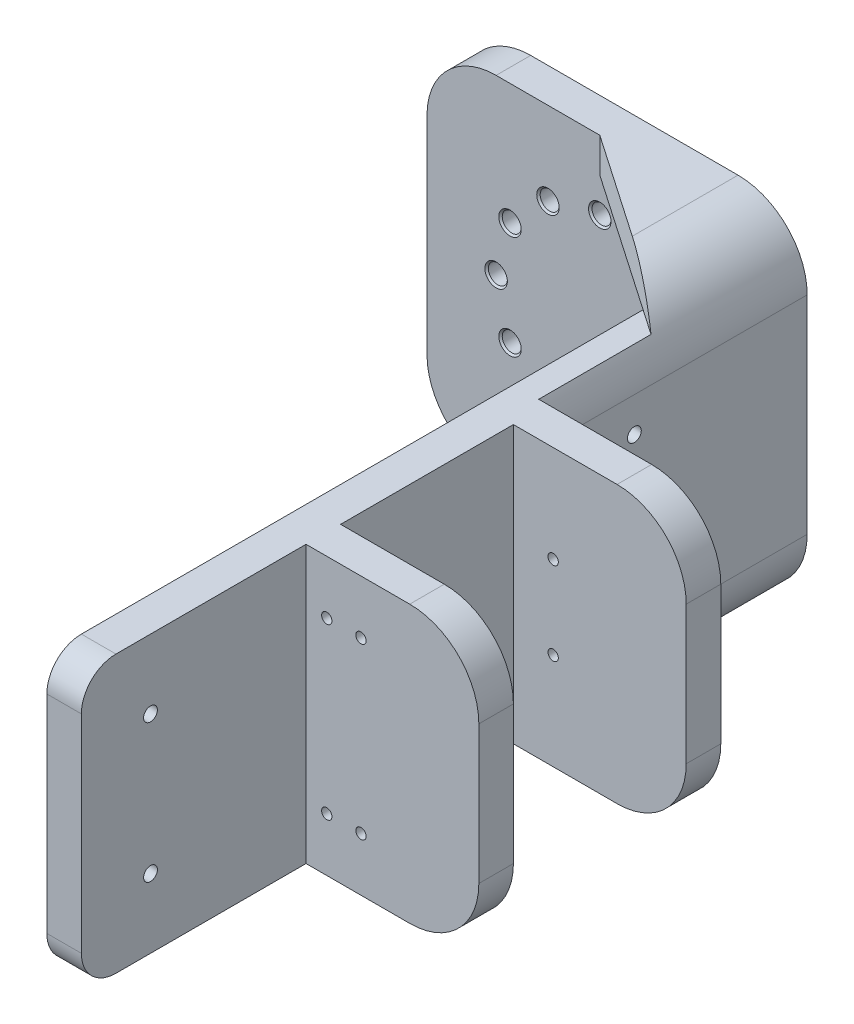
SolidWorks part; units mm, degrees
ref_plane "前视基准面" through (0, 0, 0) normal (0, 0, 1) x (1, 0, 0)
ref_plane "上视基准面" through (0, 0, 0) normal (0, 1, 0) x (1, 0, 0)
ref_plane "右视基准面" through (0, 0, 0) normal (1, 0, 0) x (0, 0, -1)
other "Configuration Table"
sketch "草图1" plane through (0, 0, 0) normal (1, 0, 0) x (0, 0, -1)
  line L1 (-100, 40) -> (100, 40)
  line L2 (-100, 40) -> (-100, -40)
  line L3 (-100, -40) -> (100, -40)
  line L4 (100, 40) -> (100, -40)
  dimension "D1" = 80
  dimension "D2" = 40
  dimension "D3" = 200
  dimension "D4" = 100
extrude "凸台-拉伸1" add sketch "草图1" along normal blind 10
sketch "草图2" plane through (10, 0, 0) normal (1, 0, 0) x (0, 0, -1)
  line L0 (100, 40) -> (-100, 40) construction
  line L1 (-35, 40) -> (-25, 40)
  line L2 (-35, 40) -> (-35, -40)
  line L3 (-35, -40) -> (-25, -40)
  line L4 (-25, 40) -> (-25, -40)
  line L5 (-100, -40) -> (100, -40) construction
  line L7 (25, 40) -> (35, 40)
  line L8 (25, 40) -> (25, -40)
  line L9 (25, -40) -> (35, -40)
  line L10 (35, 40) -> (35, -40)
  dimension "D1" = 10
  dimension "D2" = 10
  dimension "D3" = 50
  dimension "D4" = 25
extrude "凸台-拉伸2" add sketch "草图2" along normal blind 50
sketch "草图3" plane through (0, 0, -100) normal (0, 0, -1) x (-1, 0, 0)
  line L0 (0, -40) -> (0, 40) construction
  line L1 (-10, 50) -> (90, 50)
  line L2 (-10, 50) -> (-10, -50)
  line L3 (-10, -50) -> (90, -50)
  line L4 (90, 50) -> (90, -50)
  dimension "D1" = 100
  dimension "D2" = 50
  dimension "D3" = 50
  dimension "D4" = 10
extrude "凸台-拉伸3" add sketch "草图3" along normal blind 10
sketch "草图5" plane through (0, 40, 0) normal (0, 1, 0) x (1, 0, 0)
  line L0 (10, 55) -> (-15, 100)
  line L1 (10, 100) -> (10, 35) construction
  line L2 (-90, 100) -> (10, 100) construction
  line L3 (-15, 100) -> (10, 100)
  line L4 (10, 100) -> (10, 55)
  dimension "D1" = 45
  dimension "D2" = 25
extrude "凸台-拉伸4" add sketch "草图5" against normal blind 15
sketch "草图6" plane through (0, -40, 0) normal (0, -1, 0) x (1, 0, 0)
  line L3 (-15, -100) -> (0, -100)
  line L4 (0, -100) -> (0, -73)
  line L5 (0, -73) -> (-15, -100)
  line L6 (-15, -100) -> (0, -100)
  line L7 (0, -100) -> (0, -73)
  line L8 (0, -73) -> (-15, -100)
  dimension "D1" = 0
extrude "凸台-拉伸5" add sketch "草图6" against normal blind 15
fillet "圆角1" radius 20 4 edges at (10, 50, -105) (10, -50, -105) (-90, 50, -105) (-90, -50, -105)
sketch "草图7" plane through (0, 0, -110) normal (0, 0, -1) x (-1, 0, 0)
  line L0 (70, 50) -> (10, 50) construction
  line L1 (90, -30) -> (90, 30) construction
  circle A0 centre (40, 0) radius 30 construction
  circle A1 centre (40, 30) radius 2.75
  circle A2 centre (10, 0) radius 2.75
  circle A3 centre (70, 0) radius 2.75
  circle A4 centre (40, -30) radius 2.75
  dimension "D1" = 60
  dimension "D4" = 5.5
  dimension "D5" = 5.5
  dimension "D6" = 5.5
  dimension "D7" = 5.5
  dimension "D2" = 50
  dimension "50" = 50
extrude "切除-拉伸1" cut sketch "草图7" against normal blind 15
sketch "草图8" plane through (0, 0, -35) normal (0, 0, -1) x (-1, 0, 0)
  line L0 (-10, -30) -> (-10, 30) construction
  line L1 (-16, 24.5) -> (-25.9, 24.5) construction
  line L2 (-16, 24.5) -> (-16, -24.5) construction
  line L3 (-16, -24.5) -> (-25.9, -24.5) construction
  line L4 (-25.9, 24.5) -> (-25.9, -24.5) construction
  circle A0 centre (-16, 24.5) radius 1.5
  circle A1 centre (-25.9, 24.5) radius 1.5
  circle A2 centre (-16, -24.5) radius 1.5
  circle A3 centre (-25.9, -24.5) radius 1.5
  dimension "D5" = 3
  dimension "D1" = 9.9
  dimension "D2" = 49
  dimension "D3" = 24.5
  dimension "D4" = 6
extrude "切除-拉伸2" cut sketch "草图8" against normal blind 15 from offset 60 offset against normal yes
sketch "草图9" plane through (0, 0, 35) normal (0, 0, 1) x (1, 0, 0)
  line L0 (10, 40) -> (10, -40) construction
  circle A0 centre (21.5, 12) radius 1.5
  circle A1 centre (21.5, -12) radius 1.5
  dimension "D1" = 3
  dimension "D2" = 3
  dimension "D3" = 24
  dimension "D4" = 11.5
  dimension "D5" = 12
extrude "切除-拉伸3" cut sketch "草图9" against normal blind 15 from offset 60 offset against normal yes
fillet "圆角2" radius 20 4 edges at (60, -40, -30) (60, 40, -30) (60, -40, 30) (60, 40, 30)
sketch "草图16" plane through (0, 0, -100) normal (0, 0, 1) x (1, 0, 0)
  line L1 (-40, 0) -> (49960, 0) construction
  line L2 (-40, 0) -> (-40, 50000) construction
  line L3 (-40, 0) -> (24960, 43301.2702) construction
  line L4 (-40, 0) -> (43261.2702, 25000) construction
  line L5 (0, -25) -> (0, 25) construction
  circle A0 centre (-40, 0) radius 30 construction
  circle A1 centre (-25, 25.9808) radius 2.75
  circle A2 centre (-14.0192, 15) radius 2.75
  circle A3 centre (-25, -25.9808) radius 2.75
  circle A4 centre (-14.0192, -15) radius 2.75
  circle A5 centre (-55, 25.9808) radius 2.75
  circle A6 centre (-65.9808, 15) radius 2.75
  circle A7 centre (-55, -25.9808) radius 2.75
  circle A8 centre (-65.9808, -15) radius 2.75
  dimension "D1" = 30
  dimension "D3" = 5.5
  dimension "D4" = 5.5
  dimension "D2" = 30
  dimension "D5" = 40
extrude "切除-拉伸7" cut sketch "草图16" against normal through all
chamfer "倒角2" distance 0.5 angle 45 12 edges at (-40, -27.25, -100) (-40, -27.25, -110) (-52.25, -25.9808, -100) (-52.25, -25.9808, -110) (-63.2308, -15, -100) (-63.2308, -15, -110) (-70, 2.75, -100) (-70, 2.75, -110) (-68.7308, 15, -100) (-68.7308, 15, -110) (-57.75, 25.9808, -100) (-57.75, 25.9808, -110)
chamfer "倒角3" distance 0.5 angle 45 12 edges at (-40, 32.75, -100) (-40, 32.75, -110) (-22.25, 25.9808, -100) (-22.25, 25.9808, -110) (-11.2692, 15, -100) (-11.2692, 15, -110) (-10, 2.75, -100) (-10, 2.75, -110) (-16.7692, -15, -100) (-16.7692, -15, -110) (-27.75, -25.9808, -100) (-27.75, -25.9808, -110)
sketch "草图17" plane through (0, -40, 0) normal (0, -1, 0) x (1, 0, 0)
  line L0 (7.3205, -100) -> (-40, -100)
  line L1 (-10, -100) -> (-70, -100) construction
  line L2 (-40, -100) -> (7.3205, -67.5)
  line L3 (7.3205, -100) -> (7.3205, -35) construction
  line L4 (7.3205, -67.5) -> (7.3205, -100)
extrude "凸台-拉伸8" add sketch "草图17" along normal blind 10
sketch "草图18" plane through (0, 0, -100) normal (0, 0, -1) x (-1, 0, 0)
  line L2 (-7.3205, -40) -> (-7.3205, -50)
  line L3 (-7.3205, -50) -> (10, -50)
  line L4 (-7.3205, -40) -> (-7.3205, -50)
  line L5 (-7.3205, -50) -> (10, -50)
  arc A1 (-7.3205, -40) -> (10, -50) centre (10, -30) ccw
  arc A2 (-7.3205, -40) -> (10, -50) centre (10, -30) ccw
  dimension "D1" = 0
extrude "切除-拉伸8" cut sketch "草图18" against normal through all
mirror "镜向2" about plane through (0, 0, 0) normal (0, 1, 0) of "凸台-拉伸8"
sketch "草图19" plane through (0, 0, -100) normal (0, 0, -1) x (-1, 0, 0)
  line L2 (-7.3205, 50) -> (-7.3205, 40)
  line L3 (10, 50) -> (-7.3205, 50)
  line L4 (-7.3205, 50) -> (-7.3205, 40)
  line L5 (10, 50) -> (-7.3205, 50)
  arc A1 (10, 50) -> (-7.3205, 40) centre (10, 30) ccw
  arc A2 (10, 50) -> (-7.3205, 40) centre (10, 30) ccw
  dimension "D1" = 0
extrude "切除-拉伸9" cut sketch "草图19" against normal through all
sketch "草图20" plane through (0, 0, 0) normal (-1, 0, 0) x (0, 0, 1)
  line L1 (-60, 20) -> (80, 20) construction
  line L2 (-60, 20) -> (-60, -20) construction
  line L3 (-60, -20) -> (80, -20) construction
  line L4 (80, 20) -> (80, -20) construction
  circle A0 centre (80, 20) radius 2
  circle A1 centre (80, -20) radius 2
  circle A2 centre (-60, 20) radius 2
  circle A3 centre (-60, -20) radius 2
  dimension "D1" = 4
  dimension "D2" = 4
  dimension "D3" = 4
  dimension "D4" = 4
  dimension "D5" = 40
  dimension "D6" = 20
  dimension "D7" = 140
  dimension "D8" = 60
extrude "切除-拉伸10" cut sketch "草图20" against normal through all
fillet "圆角3" radius 10 2 edges at (5, 40, 100) (5, -40, 100)
